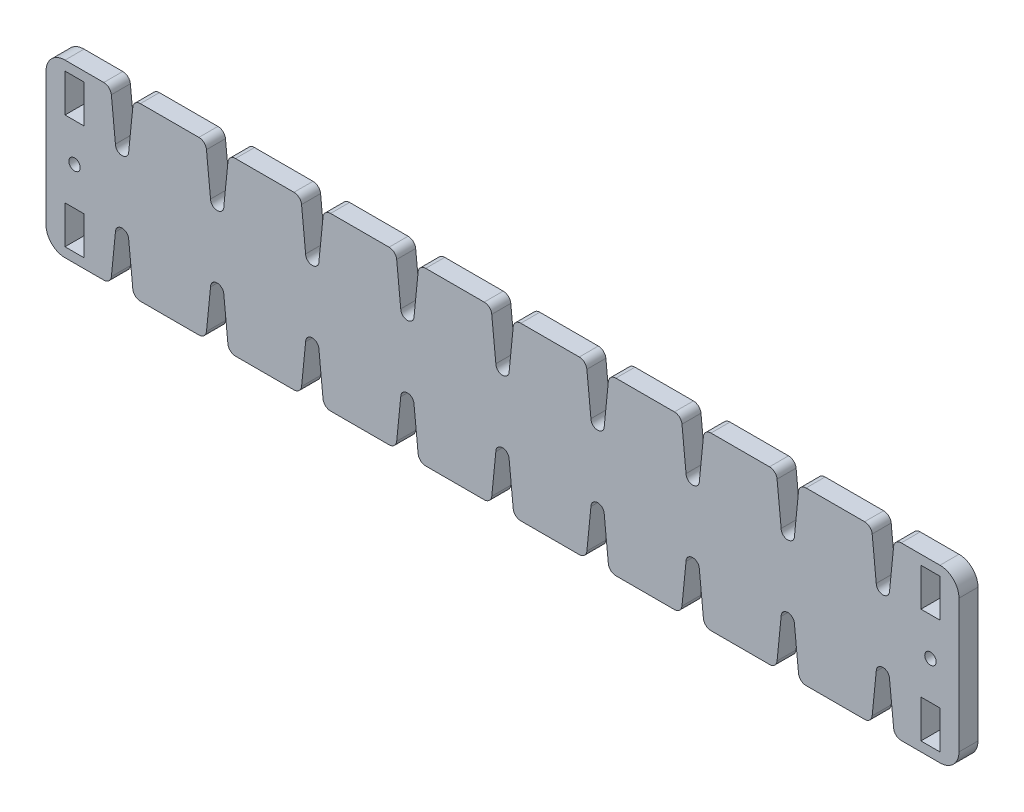
SolidWorks part; units mm, degrees
ref_plane "Front Plane" through (0, 0, 0) normal (0, 0, 1) x (1, 0, 0)
ref_plane "Top Plane" through (0, 0, 0) normal (0, 1, 0) x (1, 0, 0)
ref_plane "Right Plane" through (0, 0, 0) normal (1, 0, 0) x (0, 0, -1)
sketch "Sketch1" plane through (0, 0, 0) normal (0, 0, 1) x (1, 0, 0)
  line L0 (-90.218, 10) -> (299.3045, 10) construction
  line L1 (-85.8133, 22.5) -> (154.1867, 22.5)
  line L2 (-85.8133, 22.5) -> (-85.8133, -22.5)
  line L3 (-85.8133, -22.5) -> (154.1867, -22.5)
  line L4 (154.1867, 22.5) -> (154.1867, -22.5)
  line L5 (-80.8133, -10) -> (-75.8133, -10)
  line L6 (-91.3268, 0) -> (299.3045, 0) construction
  line L7 (-80.8133, 20) -> (-75.8133, 20)
  line L8 (-80.8133, 20) -> (-80.8133, 10)
  line L9 (-80.8133, 10) -> (-75.8133, 10)
  line L10 (-75.8133, 20) -> (-75.8133, 10)
  line L11 (-75.8133, -20) -> (-75.8133, -10)
  line L12 (-80.8133, -20) -> (-75.8133, -20)
  line L13 (-80.8133, -20) -> (-80.8133, -10)
  line L14 (34.1867, 30.0157) -> (34.1867, -45.8134) construction
  line L15 (-78.3133, 24.0051) -> (-78.3133, -32.23) construction
  line L16 (149.1867, -20) -> (149.1867, -10)
  line L17 (149.1867, -20) -> (144.1867, -20)
  line L18 (144.1867, -20) -> (144.1867, -10)
  line L19 (149.1867, -10) -> (144.1867, -10)
  line L20 (149.1867, 10) -> (144.1867, 10)
  line L21 (144.1867, 20) -> (144.1867, 10)
  line L22 (149.1867, 20) -> (144.1867, 20)
  line L23 (149.1867, 20) -> (149.1867, 10)
  circle A31 centre (-78.3133, 0) radius 1.5
  circle A32 centre (146.6867, 0) radius 1.5
  point P6 (34.1867, -22.5)
  point P13 (-85.8133, 0)
  point P82 (-78.3133, 20)
  dimension "D1" = 45
  dimension "D2" = 240
  dimension "D3" = 12.5
  dimension "D4" = 10
  dimension "D7" = 5
  dimension "D8" = 5
extrude "Boss-Extrude1" add sketch "Sketch1" along normal blind 5
sketch "Sketch2" plane through (0, 0, 5) normal (0, 0, 1) x (1, 0, 0)
  line L0 (-65.8133, 26.1544) -> (-65.8133, -32.4929) construction
  line L1 (-85.8133, 22.5) -> (-85.8133, -22.5) construction
  line L2 (154.1867, 22.5) -> (-85.8133, 22.5) construction
  line L3 (-68.8133, 22.5) -> (-62.8133, 22.5)
  line L4 (-68.8133, 22.5) -> (-67.5633, 10)
  line L6 (-62.8133, 22.5) -> (-64.0633, 10)
  line L7 (-86.9763, 0) -> (351.4175, 0) construction
  line L8 (-43.8133, 22.5) -> (-37.8133, 22.5)
  line L9 (-43.8133, 22.5) -> (-42.5633, 10)
  line L10 (-37.8133, 22.5) -> (-39.0633, 10)
  line L11 (-18.8133, 22.5) -> (-12.8133, 22.5)
  line L12 (-18.8133, 22.5) -> (-17.5633, 10)
  line L13 (-12.8133, 22.5) -> (-14.0633, 10)
  line L14 (6.1867, 22.5) -> (12.1867, 22.5)
  line L15 (6.1867, 22.5) -> (7.4367, 10)
  line L16 (12.1867, 22.5) -> (10.9367, 10)
  line L17 (31.1867, 22.5) -> (37.1867, 22.5)
  line L18 (31.1867, 22.5) -> (32.4367, 10)
  line L19 (37.1867, 22.5) -> (35.9367, 10)
  line L20 (56.1867, 22.5) -> (62.1867, 22.5)
  line L21 (56.1867, 22.5) -> (57.4367, 10)
  line L22 (62.1867, 22.5) -> (60.9367, 10)
  line L23 (81.1867, 22.5) -> (87.1867, 22.5)
  line L24 (81.1867, 22.5) -> (82.4367, 10)
  line L25 (87.1867, 22.5) -> (85.9367, 10)
  line L26 (106.1867, 22.5) -> (112.1867, 22.5)
  line L27 (106.1867, 22.5) -> (107.4367, 10)
  line L28 (112.1867, 22.5) -> (110.9367, 10)
  line L29 (131.1867, 22.5) -> (137.1867, 22.5)
  line L30 (131.1867, 22.5) -> (132.4367, 10)
  line L31 (137.1867, 22.5) -> (135.9367, 10)
  line L68 (137.1867, -22.5) -> (135.9367, -10)
  line L69 (131.1867, -22.5) -> (132.4367, -10)
  line L70 (131.1867, -22.5) -> (137.1867, -22.5)
  line L71 (112.1867, -22.5) -> (110.9367, -10)
  line L72 (106.1867, -22.5) -> (107.4367, -10)
  line L73 (106.1867, -22.5) -> (112.1867, -22.5)
  line L74 (87.1867, -22.5) -> (85.9367, -10)
  line L75 (81.1867, -22.5) -> (82.4367, -10)
  line L76 (81.1867, -22.5) -> (87.1867, -22.5)
  line L77 (62.1867, -22.5) -> (60.9367, -10)
  line L78 (56.1867, -22.5) -> (57.4367, -10)
  line L79 (56.1867, -22.5) -> (62.1867, -22.5)
  line L80 (37.1867, -22.5) -> (35.9367, -10)
  line L81 (31.1867, -22.5) -> (32.4367, -10)
  line L82 (31.1867, -22.5) -> (37.1867, -22.5)
  line L83 (12.1867, -22.5) -> (10.9367, -10)
  line L84 (6.1867, -22.5) -> (7.4367, -10)
  line L85 (6.1867, -22.5) -> (12.1867, -22.5)
  line L86 (-12.8133, -22.5) -> (-14.0633, -10)
  line L87 (-18.8133, -22.5) -> (-17.5633, -10)
  line L88 (-18.8133, -22.5) -> (-12.8133, -22.5)
  line L89 (-37.8133, -22.5) -> (-39.0633, -10)
  line L90 (-43.8133, -22.5) -> (-42.5633, -10)
  line L91 (-43.8133, -22.5) -> (-37.8133, -22.5)
  line L92 (-62.8133, -22.5) -> (-64.0633, -10)
  line L93 (-68.8133, -22.5) -> (-67.5633, -10)
  line L94 (-68.8133, -22.5) -> (-62.8133, -22.5)
  line L95 (-69.6736, 10) -> (-56.4603, 10) construction
  arc A0 (-67.5633, 10) -> (-64.0633, 10) centre (-65.8133, 10) ccw
  arc A1 (-42.5633, 10) -> (-39.0633, 10) centre (-40.8133, 10) ccw
  arc A2 (-17.5633, 10) -> (-14.0633, 10) centre (-15.8133, 10) ccw
  arc A3 (7.4367, 10) -> (10.9367, 10) centre (9.1867, 10) ccw
  arc A4 (32.4367, 10) -> (35.9367, 10) centre (34.1867, 10) ccw
  arc A5 (57.4367, 10) -> (60.9367, 10) centre (59.1867, 10) ccw
  arc A6 (82.4367, 10) -> (85.9367, 10) centre (84.1867, 10) ccw
  arc A7 (107.4367, 10) -> (110.9367, 10) centre (109.1867, 10) ccw
  arc A8 (132.4367, 10) -> (135.9367, 10) centre (134.1867, 10) ccw
  arc A21 (132.4367, -10) -> (135.9367, -10) centre (134.1867, -10) cw
  arc A22 (107.4367, -10) -> (110.9367, -10) centre (109.1867, -10) cw
  arc A23 (82.4367, -10) -> (85.9367, -10) centre (84.1867, -10) cw
  arc A24 (57.4367, -10) -> (60.9367, -10) centre (59.1867, -10) cw
  arc A25 (32.4367, -10) -> (35.9367, -10) centre (34.1867, -10) cw
  arc A26 (7.4367, -10) -> (10.9367, -10) centre (9.1867, -10) cw
  arc A27 (-17.5633, -10) -> (-14.0633, -10) centre (-15.8133, -10) cw
  arc A28 (-42.5633, -10) -> (-39.0633, -10) centre (-40.8133, -10) cw
  arc A29 (-67.5633, -10) -> (-64.0633, -10) centre (-65.8133, -10) cw
  point P10 (-65.8133, 22.5)
  dimension "D1" = 20
  dimension "D2" = 6
  dimension "D3" = 9
  dimension "D4" = 3.5
extrude "Cut-Extrude1" cut sketch "Sketch2" against normal blind 5
fillet "Fillet1" radius 2 36 edges at (-62.8133, -22.5, 2.5) (-68.8133, -22.5, 2.5) (-37.8133, -22.5, 2.5) (-43.8133, -22.5, 2.5) (-12.8133, -22.5, 2.5) (-18.8133, -22.5, 2.5) (12.1867, -22.5, 2.5) (6.1867, -22.5, 2.5) (37.1867, -22.5, 2.5) (31.1867, -22.5, 2.5) (62.1867, -22.5, 2.5) (56.1867, -22.5, 2.5) (87.1867, -22.5, 2.5) (81.1867, -22.5, 2.5) (106.1867, -22.5, 2.5) (112.1867, -22.5, 2.5) (131.1867, -22.5, 2.5) (137.1867, -22.5, 2.5) (137.1867, 22.5, 2.5) (131.1867, 22.5, 2.5) (112.1867, 22.5, 2.5) (106.1867, 22.5, 2.5) (87.1867, 22.5, 2.5) (81.1867, 22.5, 2.5) (62.1867, 22.5, 2.5) (37.1867, 22.5, 2.5) (56.1867, 22.5, 2.5) (31.1867, 22.5, 2.5) (12.1867, 22.5, 2.5) (6.1867, 22.5, 2.5) (-12.8133, 22.5, 2.5) (-18.8133, 22.5, 2.5) (-37.8133, 22.5, 2.5) (-43.8133, 22.5, 2.5) (-68.8133, 22.5, 2.5) (-62.8133, 22.5, 2.5)
fillet "Congé1" radius 5 4 edges at (-85.8133, -22.5, 2.5) (-85.8133, 22.5, 2.5) (154.1867, -22.5, 2.5) (154.1867, 22.5, 2.5)
